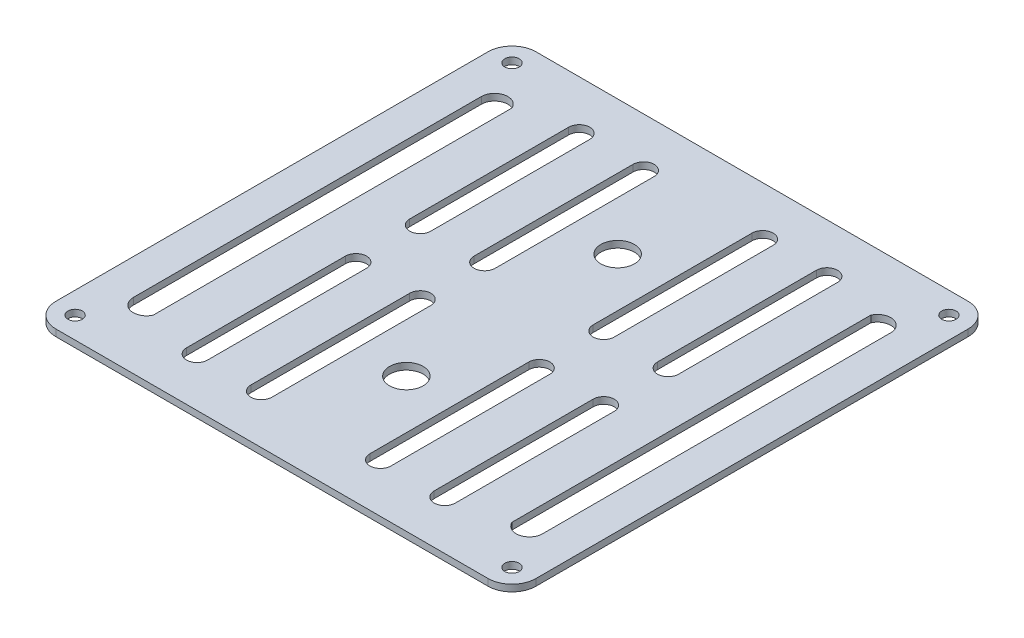
SolidWorks part; units mm, degrees
material "Thornel VCB-20 Carbon Cloth"
ref_plane "Front Plane" through (0, 0, 0) normal (0, 0, 1) x (1, 0, 0)
ref_plane "Top Plane" through (0, 0, 0) normal (0, 1, 0) x (1, 0, 0)
ref_plane "Right Plane" through (0, 0, 0) normal (1, 0, 0) x (0, 0, -1)
sketch "Sketch1" plane through (0, 0, 0) normal (0, 1, 0) x (1, 0, 0)
  line L0 (-45.5, 45.5) -> (45.5, 45.5) construction
  line L1 (50, -50) -> (-50, -50)
  line L2 (50, -50) -> (50, 50)
  line L3 (50, 50) -> (-50, 50)
  line L4 (-50, -50) -> (-50, 50)
  line L5 (50, -50) -> (-50, 50) construction
  line L6 (50, 50) -> (-50, -50) construction
  line L7 (-45.5, 45.5) -> (-45.5, -45.5) construction
  line L8 (-42.6263, 36.25) -> (-42.6263, -36.25)
  line L9 (-37.3604, 37.3604) -> (-37.3604, -37.3604)
  line L10 (0, -50) -> (0, 50) construction
  line L11 (-50, 0) -> (50, 0) construction
  line L12 (-28, 39.8) -> (-28, 6.7)
  line L13 (-23.6, 39.8) -> (-23.6, 6.7)
  line L14 (-14.6, 39.8) -> (-14.6, 6.7)
  line L15 (-10.2, 39.8) -> (-10.2, 6.7)
  line L16 (-10.2, -39.8) -> (-10.2, -6.7)
  line L17 (-14.6, -39.8) -> (-14.6, -6.7)
  line L18 (-23.6, -39.8) -> (-23.6, -6.7)
  line L19 (-28, -39.8) -> (-28, -6.7)
  line L20 (10.2, -39.8) -> (10.2, -6.7)
  line L21 (14.6, -39.8) -> (14.6, -6.7)
  line L22 (10.2, 39.8) -> (10.2, 6.7)
  line L23 (14.6, 39.8) -> (14.6, 6.7)
  line L24 (23.6, -39.8) -> (23.6, -6.7)
  line L25 (28, -39.8) -> (28, -6.7)
  line L26 (23.6, 39.8) -> (23.6, 6.7)
  line L27 (37.3604, 37.3604) -> (37.3604, -37.3604)
  line L28 (28, 39.8) -> (28, 6.7)
  line L29 (42.6263, 36.25) -> (42.6263, -36.25)
  circle A0 centre (-45.5, 45.5) radius 1.5
  circle A1 centre (45.5, 45.5) radius 1.5
  circle A2 centre (-45.5, -45.5) radius 1.5
  circle A3 centre (45.5, -45.5) radius 1.5
  arc A4 (-37.3604, 37.3604) -> (-42.6263, 36.25) centre (-39.8763, 36.25) ccw
  arc A5 (-42.6263, -36.25) -> (-37.3604, -37.3604) centre (-39.8763, -36.25) ccw
  arc A6 (-23.6, 39.8) -> (-28, 39.8) centre (-25.8, 39.8) ccw
  arc A7 (-28, 6.7) -> (-23.6, 6.7) centre (-25.8, 6.7) ccw
  arc A8 (-10.2, 39.8) -> (-14.6, 39.8) centre (-12.4, 39.8) ccw
  arc A9 (-14.6, 6.7) -> (-10.2, 6.7) centre (-12.4, 6.7) ccw
  arc A10 (-14.6, -6.7) -> (-10.2, -6.7) centre (-12.4, -6.7) cw
  arc A11 (-10.2, -39.8) -> (-14.6, -39.8) centre (-12.4, -39.8) cw
  arc A12 (-28, -6.7) -> (-23.6, -6.7) centre (-25.8, -6.7) cw
  arc A13 (-23.6, -39.8) -> (-28, -39.8) centre (-25.8, -39.8) cw
  arc A14 (10.2, -39.8) -> (14.6, -39.8) centre (12.4, -39.8) ccw
  arc A15 (14.6, -6.7) -> (10.2, -6.7) centre (12.4, -6.7) ccw
  arc A16 (14.6, 6.7) -> (10.2, 6.7) centre (12.4, 6.7) cw
  arc A17 (10.2, 39.8) -> (14.6, 39.8) centre (12.4, 39.8) cw
  arc A18 (23.6, -39.8) -> (28, -39.8) centre (25.8, -39.8) ccw
  arc A19 (28, -6.7) -> (23.6, -6.7) centre (25.8, -6.7) ccw
  arc A20 (28, 6.7) -> (23.6, 6.7) centre (25.8, 6.7) cw
  arc A21 (23.6, 39.8) -> (28, 39.8) centre (25.8, 39.8) cw
  arc A22 (42.6263, -36.25) -> (37.3604, -37.3604) centre (39.8763, -36.25) cw
  arc A23 (37.3604, 37.3604) -> (42.6263, 36.25) centre (39.8763, 36.25) cw
  circle A24 centre (0, 22) radius 3.5
  circle A25 centre (0, -22) radius 3.5
  point P0 (0, 0)
  point P14 (0, 45.5)
  point P15 (0, 50)
  point P16 (-50, 0)
  point P17 (-45.5, 0)
  point P26 (-42.6263, 0)
  dimension "D5" = 3
  dimension "D6" = 3
  dimension "D7" = 3
  dimension "D8" = 3
  dimension "D9" = 5.5
  dimension "D10" = 5.5
  dimension "D12" = 4.4
  dimension "D13" = 4.4
  dimension "D19" = 7
  dimension "D1" = 100
  dimension "D2" = 100
  dimension "D3" = 91
  dimension "D4" = 91
  dimension "D11" = 72.5
  dimension "D14" = 33.1
  dimension "D15" = 22
  dimension "D16" = 10.2
  dimension "D18" = 9
  dimension "D20" = 28
  dimension "D17" = 2
extrude "Boss-Extrude1" add sketch "Sketch1" along normal blind 1.4
fillet "Fillet1" radius 5 4 edges at (-50, 0.7, 50) (50, 0.7, 50) (50, 0.7, -50) (-50, 0.7, -50)
